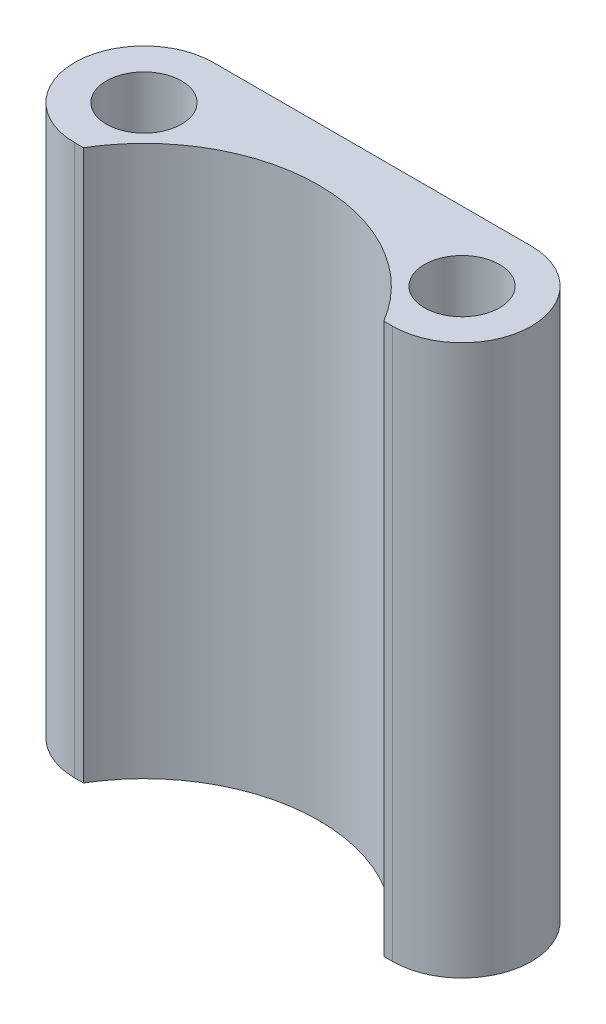
SolidWorks part; units mm, degrees
ref_plane "Front Plane" through (0, 0, 0) normal (0, 0, 1) x (1, 0, 0)
ref_plane "Top Plane" through (0, 0, 0) normal (0, 1, 0) x (1, 0, 0)
ref_plane "Right Plane" through (0, 0, 0) normal (1, 0, 0) x (0, 0, -1)
sketch "Sketch1" plane through (0, 0, 0) normal (0, 1, 0) x (1, 0, 0)
  line L0 (-12.7, 0) -> (12.7, 0)
  line L1 (-12.7, 0) -> (12.7, 0) construction
  line L2 (-12.7, 5.54) -> (12.7, 5.54)
  line L3 (-12.7, -5.54) -> (12.7, -5.54)
  circle A0 centre (-12.7, 0) radius 3
  circle A1 centre (12.7, 0) radius 3
  arc A2 (-12.7, 5.54) -> (-12.7, -5.54) centre (-12.7, 0) ccw
  arc A3 (12.7, -5.54) -> (12.7, 5.54) centre (12.7, 0) ccw
  circle A5 centre (0, -12.7) radius 13.97
  point P2 (0, 0)
  point P6 (0, 0)
  dimension "D2" = 6
  dimension "D3" = 6
  dimension "D4" = 2.54
  dimension "D5" = 27.94
  dimension "D1" = 25.4
extrude "Boss-Extrude1" add sketch "Sketch1" along normal blind 43.942
